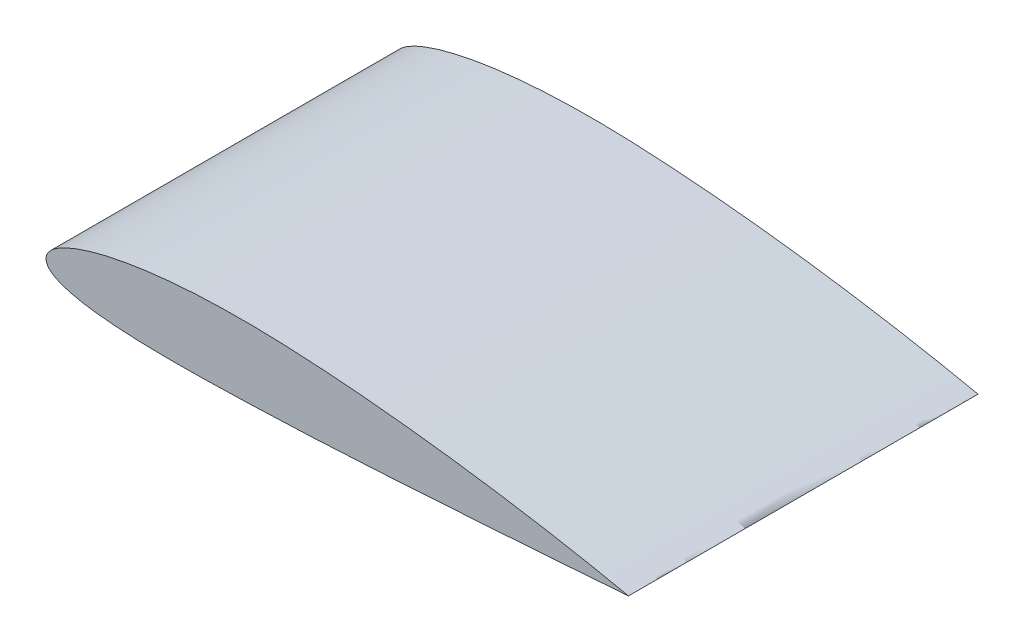
SolidWorks part; units mm, degrees
ref_plane "Front Plane" through (0, 0, 0) normal (1, 0, 0) x (0, 1, 0)
ref_plane "Top Plane" through (0, 0, 0) normal (0, 0, 1) x (0, 1, 0)
ref_plane "Right Plane" through (0, 0, 0) normal (0, 1, 0) x (-1, 0, 0)
curve "Curve1"
  spline degree 3 poles (0.9995, 0, 0) (1.0001, 0, 0) (0.9995, 0.0001, 0) (0.9989, 0.0002, 0) (0.9976, 0.0005, 0) (0.9959, 0.0009, 0) (0.9937, 0.0013, 0) (0.9911, 0.0019, 0) (0.9879, 0.0026, 0) (0.9843, 0.0033, 0) (0.9802, 0.0042, 0) (0.9756, 0.0051, 0) (0.9706, 0.0062, 0) (0.965, 0.0073, 0) (0.9591, 0.0085, 0) (0.9527, 0.0098, 0) (0.9458, 0.0111, 0) (0.9385, 0.0126, 0) (0.9308, 0.0141, 0) (0.9227, 0.0156, 0) (0.9141, 0.0173, 0) (0.9051, 0.0189, 0) (0.8957, 0.0207, 0) (0.886, 0.0224, 0) (0.8758, 0.0243, 0) (0.8653, 0.0261, 0) (0.8544, 0.028, 0) (0.8432, 0.0299, 0) (0.8316, 0.0319, 0) (0.8197, 0.0338, 0) (0.8075, 0.0358, 0) (0.795, 0.0378, 0) (0.7821, 0.0398, 0) (0.769, 0.0418, 0) (0.7556, 0.0437, 0) (0.742, 0.0457, 0) (0.7281, 0.0477, 0) (0.714, 0.0496, 0) (0.6997, 0.0515, 0) (0.6852, 0.0534, 0) (0.6705, 0.0553, 0) (0.6556, 0.0571, 0) (0.6406, 0.0589, 0) (0.6254, 0.0606, 0) (0.6101, 0.0623, 0) (0.5947, 0.0639, 0) (0.5791, 0.0655, 0) (0.5635, 0.067, 0) (0.5479, 0.0684, 0) (0.5321, 0.0698, 0) (0.5164, 0.0711, 0) (0.5006, 0.0723, 0) (0.4848, 0.0735, 0) (0.469, 0.0745, 0) (0.4533, 0.0755, 0) (0.4376, 0.0763, 0) (0.4219, 0.0771, 0) (0.4064, 0.0778, 0) (0.3908, 0.0783, 0) (0.3753, 0.0788, 0) (0.36, 0.0791, 0) (0.3447, 0.0792, 0) (0.3297, 0.0792, 0) (0.3147, 0.0791, 0) (0.3, 0.0788, 0) (0.2855, 0.0784, 0) (0.2712, 0.0778, 0) (0.2571, 0.0771, 0) (0.2433, 0.0763, 0) (0.2297, 0.0753, 0) (0.2164, 0.0742, 0) (0.2034, 0.073, 0) (0.1907, 0.0716, 0) (0.1783, 0.0701, 0) (0.1663, 0.0685, 0) (0.1546, 0.0668, 0) (0.1432, 0.065, 0) (0.1322, 0.0631, 0) (0.1216, 0.061, 0) (0.1114, 0.0589, 0) (0.1015, 0.0567, 0) (0.0921, 0.0544, 0) (0.0831, 0.052, 0) (0.0745, 0.0496, 0) (0.0664, 0.0471, 0) (0.0587, 0.0445, 0) (0.0514, 0.0419, 0) (0.0446, 0.0392, 0) (0.0383, 0.0365, 0) (0.0325, 0.0338, 0) (0.0271, 0.031, 0) (0.0221, 0.0283, 0) (0.0177, 0.0255, 0) (0.0138, 0.0226, 0) (0.0103, 0.0198, 0) (0.0073, 0.017, 0) (0.0048, 0.0142, 0) (0.0029, 0.0113, 0) (0.0014, 0.0085, 0) (0.0004, 0.0057, 0) (-0.0001, 0.0028, 0) (-0.0001, 0, 0) (0.0004, -0.0028, 0) (0.0015, -0.0055, 0) (0.003, -0.0081, 0) (0.005, -0.0106, 0) (0.0075, -0.0129, 0) (0.0105, -0.0152, 0) (0.0139, -0.0174, 0) (0.0178, -0.0196, 0) (0.0222, -0.0216, 0) (0.027, -0.0235, 0) (0.0323, -0.0253, 0) (0.038, -0.0271, 0) (0.0442, -0.0287, 0) (0.0508, -0.0303, 0) (0.0578, -0.0317, 0) (0.0652, -0.0331, 0) (0.0731, -0.0343, 0) (0.0814, -0.0355, 0) (0.09, -0.0366, 0) (0.0991, -0.0375, 0) (0.1085, -0.0384, 0) (0.1184, -0.0392, 0) (0.1285, -0.0399, 0) (0.139, -0.0405, 0) (0.1499, -0.041, 0) (0.1611, -0.0415, 0) (0.1726, -0.0418, 0) (0.1845, -0.0421, 0) (0.1966, -0.0423, 0) (0.209, -0.0424, 0) (0.2217, -0.0424, 0) (0.2346, -0.0423, 0) (0.2478, -0.0422, 0) (0.2613, -0.0421, 0) (0.275, -0.0418, 0) (0.2889, -0.0415, 0) (0.303, -0.0412, 0) (0.3173, -0.0408, 0) (0.3317, -0.0404, 0) (0.3464, -0.0399, 0) (0.3611, -0.0394, 0) (0.3761, -0.0389, 0) (0.3911, -0.0383, 0) (0.4063, -0.0378, 0) (0.4217, -0.0371, 0) (0.4371, -0.0365, 0) (0.4526, -0.0358, 0) (0.4682, -0.035, 0) (0.4838, -0.0342, 0) (0.4994, -0.0334, 0) (0.515, -0.0326, 0) (0.5306, -0.0317, 0) (0.5462, -0.0308, 0) (0.5618, -0.0299, 0) (0.5773, -0.029, 0) (0.5927, -0.0281, 0) (0.608, -0.0271, 0) (0.6232, -0.0262, 0) (0.6383, -0.0252, 0) (0.6533, -0.0243, 0) (0.6681, -0.0233, 0) (0.6828, -0.0224, 0) (0.6973, -0.0214, 0) (0.7116, -0.0205, 0) (0.7257, -0.0195, 0) (0.7396, -0.0186, 0) (0.7532, -0.0177, 0) (0.7666, -0.0168, 0) (0.7798, -0.0159, 0) (0.7926, -0.015, 0) (0.8052, -0.0141, 0) (0.8175, -0.0133, 0) (0.8295, -0.0125, 0) (0.8411, -0.0116, 0) (0.8525, -0.0109, 0) (0.8634, -0.0101, 0) (0.874, -0.0093, 0) (0.8843, -0.0086, 0) (0.8942, -0.0079, 0) (0.9036, -0.0072, 0) (0.9127, -0.0065, 0) (0.9214, -0.0059, 0) (0.9297, -0.0053, 0) (0.9375, -0.0047, 0) (0.9449, -0.0042, 0) (0.9519, -0.0037, 0) (0.9584, -0.0032, 0) (0.9644, -0.0027, 0) (0.97, -0.0023, 0) (0.9751, -0.0019, 0) (0.9798, -0.0016, 0) (0.984, -0.0012, 0) (0.9877, -0.001, 0) (0.9909, -0.0007, 0) (0.9936, -0.0005, 0) (0.9959, -0.0003, 0) (0.9976, -0.0002, 0) (0.9989, -0.0001, 0) (0.9995, 0, 0) (1.0001, 0, 0) (0.9995, 0.0001, 0) knots -0.0011 -0.000489 -0.000122 0 0.000122 0.000489 0.001101 0.001956 0.003053 0.004392 0.005972 0.007791 0.009846 0.012136 0.014659 0.017411 0.020391 0.023594 0.02702 0.030662 0.034518 0.038584 0.042857 0.04733 0.052001 0.056865 0.061917 0.067151 0.072562 0.078146 0.083896 0.089808 0.095874 0.102089 0.108447 0.114942 0.121567 0.128315 0.13518 0.142156 0.149234 0.156409 0.163672 0.171018 0.178438 0.185926 0.193473 0.201072 0.208716 0.216398 0.224109 0.231843 0.23959 0.247345 0.255098 0.262842 0.27057 0.278275 0.285948 0.293582 0.301205 0.308799 0.316332 0.323797 0.331187 0.338493 0.345709 0.352829 0.359844 0.36675 0.373538 0.380203 0.386738 0.393139 0.399397 0.405507 0.411466 0.417265 0.422901 0.428369 0.433664 0.438782 0.443717 0.448468 0.453029 0.457397 0.461571 0.465546 0.469321 0.472895 0.476266 0.479434 0.482399 0.485163 0.487728 0.490098 0.492281 0.494284 0.49612 0.497805 0.499362 0.500818 0.502209 0.503576 0.504943 0.506334 0.507789 0.509344 0.511025 0.512853 0.514846 0.517014 0.519365 0.521906 0.524639 0.527568 0.530692 0.534013 0.537528 0.541238 0.54514 0.549232 0.553512 0.557975 0.562619 0.567441 0.572435 0.577599 0.582928 0.588418 0.594063 0.599859 0.605801 0.611883 0.618101 0.624448 0.63092 0.63751 0.644213 0.651022 0.657931 0.664934 0.672025 0.679197 0.686444 0.693758 0.701134 0.708588 0.716126 0.723702 0.731312 0.738946 0.746598 0.75426 0.761925 0.769585 0.777233 0.784861 0.792462 0.800028 0.807552 0.815027 0.822444 0.829797 0.837078 0.84428 0.851396 0.85842 0.865343 0.872158 0.87886 0.885442 0.891896 0.898216 0.904397 0.910431 0.916313 0.922036 0.927595 0.932985 0.938199 0.943233 0.948081 0.952738 0.9572 0.961461 0.965519 0.969367 0.973003 0.976422 0.979622 0.982599 0.985348 0.987869 0.990157 0.992211 0.994029 0.995608 0.996947 0.998045 0.9989 0.999511 0.999878 1 1.000122 1.000489 1.001101 periodic
sketch "Sketch2" plane through (0, 0, 0) normal (0, 0, 1) x (0, 1, 0)
  spline S1 degree 3 poles (-0.0036, -149.92) (-0.0013, -150.0198) (0.0142, -149.9212) (0.0359, -149.8404) (0.0758, -149.6408) (0.1298, -149.3921) (0.2, -149.0606) (0.2845, -148.6604) (0.3844, -148.1869) (0.4983, -147.6421) (0.6268, -147.0261) (0.7687, -146.3395) (0.9243, -145.5831) (1.0927, -144.7574) (1.2734, -143.8633) (1.4664, -142.9017) (1.6704, -141.8732) (1.8853, -140.779) (2.1103, -139.6201) (2.3452, -138.3976) (2.5888, -137.1126) (2.8407, -135.7663) (3.1003, -134.36) (3.3669, -132.8951) (3.6398, -131.3729) (3.9183, -129.7949) (4.2015, -128.1625) (4.4891, -126.4775) (4.7802, -124.7413) (5.0741, -122.9557) (5.3699, -121.1222) (5.6673, -119.2428) (5.9652, -117.3192) (6.2632, -115.3534) (6.5604, -113.3472) (6.8562, -111.3025) (7.15, -109.2214) (7.4409, -107.1058) (7.7284, -104.9579) (8.0116, -102.7798) (8.2901, -100.5736) (8.563, -98.3414) (8.8298, -96.0855) (9.0899, -93.808) (9.3425, -91.5113) (9.5867, -89.1977) (9.8223, -86.8693) (10.0487, -84.5285) (10.2647, -82.1776) (10.4704, -79.8191) (10.6648, -77.4552) (10.8475, -75.0884) (11.0178, -72.7208) (11.1749, -70.3551) (11.3191, -67.9935) (11.4489, -65.6384) (11.5645, -63.2922) (11.6653, -60.9537) (11.7507, -58.6225) (11.8147, -56.3009) (11.8582, -53.995) (11.8805, -51.7098) (11.8814, -49.4476) (11.8615, -47.2108) (11.8197, -45.0019) (11.7574, -42.8232) (11.6734, -40.677) (11.5689, -38.5655) (11.4434, -36.491) (11.298, -34.4556) (11.1322, -32.4616) (10.9471, -30.511) (10.7429, -28.6059) (10.5204, -26.7482) (10.2797, -24.9401) (10.0221, -23.1832) (9.7479, -21.4796) (9.4581, -19.8307) (9.1531, -18.2385) (8.8344, -16.7044) (8.5023, -15.2301) (8.1577, -13.8171) (7.8021, -12.4666) (7.4357, -11.1801) (7.0597, -9.9587) (6.6754, -8.8037) (6.2832, -7.7161) (5.8843, -6.697) (5.4796, -5.7471) (5.0699, -4.8675) (4.656, -4.0589) (4.2389, -3.3217) (3.8191, -2.6568) (3.3973, -2.0646) (2.9744, -1.5451) (2.5502, -1.0992) (2.1255, -0.7269) (1.7004, -0.4283) (1.2746, -0.2043) (0.8483, -0.0558) (0.4221, 0.017) (-0.0013, 0.0124) (-0.417, -0.067) (-0.8205, -0.2223) (-1.209, -0.4515) (-1.5825, -0.7534) (-1.9413, -1.1271) (-2.2857, -1.5719) (-2.616, -2.0871) (-2.9325, -2.6723) (-3.2352, -3.3268) (-3.5238, -4.0501) (-3.7985, -4.8414) (-4.0591, -5.6998) (-4.3055, -6.6245) (-4.5378, -7.6146) (-4.7557, -8.669) (-4.9595, -9.7866) (-5.1487, -10.9664) (-5.3238, -12.207) (-5.4847, -13.5073) (-5.6312, -14.8661) (-5.7634, -16.2818) (-5.8821, -17.7532) (-5.9864, -19.2789) (-6.0776, -20.8573) (-6.155, -22.487) (-6.2195, -24.1664) (-6.2714, -25.8939) (-6.3104, -27.668) (-6.338, -29.4869) (-6.3533, -31.3491) (-6.3581, -33.2527) (-6.3518, -35.196) (-6.3356, -37.1772) (-6.31, -39.1947) (-6.2751, -41.2464) (-6.2321, -43.3306) (-6.1813, -45.4452) (-6.1232, -47.5885) (-6.0589, -49.7585) (-5.989, -51.9531) (-5.9136, -54.1703) (-5.8342, -56.4082) (-5.7503, -58.6672) (-5.6643, -60.9489) (-5.5709, -63.2508) (-5.4709, -65.5683) (-5.3643, -67.8954) (-5.2521, -70.2299) (-5.1347, -72.5696) (-5.0128, -74.9122) (-4.8866, -77.2554) (-4.7569, -79.5969) (-4.6237, -81.9345) (-4.4882, -84.2659) (-4.3501, -86.5888) (-4.2106, -88.9009) (-4.0694, -91.2) (-3.927, -93.4837) (-3.7843, -95.75) (-3.6411, -97.9965) (-3.4976, -100.2209) (-3.3548, -102.4212) (-3.2123, -104.5952) (-3.0707, -106.7406) (-2.9302, -108.8553) (-2.7909, -110.9373) (-2.6531, -112.9844) (-2.5171, -114.9947) (-2.3831, -116.966) (-2.2509, -118.8965) (-2.121, -120.7841) (-1.9939, -122.627) (-1.8688, -124.4233) (-1.7469, -126.1712) (-1.6276, -127.869) (-1.5116, -129.5148) (-1.3985, -131.1071) (-1.2889, -132.6442) (-1.1827, -134.1246) (-1.0802, -135.5466) (-0.9813, -136.909) (-0.8867, -138.2102) (-0.7957, -139.4489) (-0.7092, -140.6239) (-0.6271, -141.734) (-0.5492, -142.7779) (-0.4762, -143.7547) (-0.408, -144.6633) (-0.3445, -145.5028) (-0.2863, -146.2722) (-0.2329, -146.9707) (-0.1852, -147.5977) (-0.1425, -148.1524) (-0.1056, -148.6348) (-0.074, -149.0425) (-0.0482, -149.3803) (-0.0277, -149.634) (-0.0142, -149.8371) (-0.0036, -149.92) (-0.0013, -150.0198) (0.0142, -149.9212) knots -0.0011 -0.000489 -0.000122 0 0.000122 0.000489 0.001101 0.001956 0.003053 0.004392 0.005972 0.007791 0.009846 0.012136 0.014659 0.017411 0.020391 0.023594 0.02702 0.030662 0.034518 0.038584 0.042857 0.04733 0.052001 0.056865 0.061917 0.067151 0.072562 0.078146 0.083896 0.089808 0.095874 0.102089 0.108447 0.114942 0.121567 0.128315 0.13518 0.142156 0.149234 0.156409 0.163672 0.171018 0.178438 0.185926 0.193473 0.201072 0.208716 0.216398 0.224109 0.231843 0.23959 0.247345 0.255098 0.262842 0.27057 0.278275 0.285948 0.293582 0.301205 0.308799 0.316332 0.323797 0.331187 0.338493 0.345709 0.352829 0.359844 0.36675 0.373538 0.380203 0.386738 0.393139 0.399397 0.405507 0.411466 0.417265 0.422901 0.428369 0.433664 0.438782 0.443717 0.448468 0.453029 0.457397 0.461571 0.465546 0.469321 0.472895 0.476266 0.479434 0.482399 0.485163 0.487728 0.490098 0.492281 0.494284 0.49612 0.497805 0.499362 0.500818 0.502209 0.503576 0.504943 0.506334 0.507789 0.509344 0.511025 0.512853 0.514846 0.517014 0.519365 0.521906 0.524639 0.527568 0.530692 0.534013 0.537528 0.541238 0.54514 0.549232 0.553512 0.557975 0.562619 0.567441 0.572435 0.577599 0.582928 0.588418 0.594063 0.599859 0.605801 0.611883 0.618101 0.624448 0.63092 0.63751 0.644213 0.651022 0.657931 0.664934 0.672025 0.679197 0.686444 0.693758 0.701134 0.708588 0.716126 0.723702 0.731312 0.738946 0.746598 0.75426 0.761925 0.769585 0.777233 0.784861 0.792462 0.800028 0.807552 0.815027 0.822444 0.829797 0.837078 0.84428 0.851396 0.85842 0.865343 0.872158 0.87886 0.885442 0.891896 0.898216 0.904397 0.910431 0.916313 0.922036 0.927595 0.932985 0.938199 0.943233 0.948081 0.952738 0.9572 0.961461 0.965519 0.969367 0.973003 0.976422 0.979622 0.982599 0.985348 0.987869 0.990157 0.992211 0.994029 0.995608 0.996947 0.998045 0.9989 0.999511 0.999878 1 1.000122 1.000489 1.001101 only from (0, -150) to (0, -150)
extrude "Boss-Extrude1" add sketch "Sketch2" along normal blind 90 contours S1
